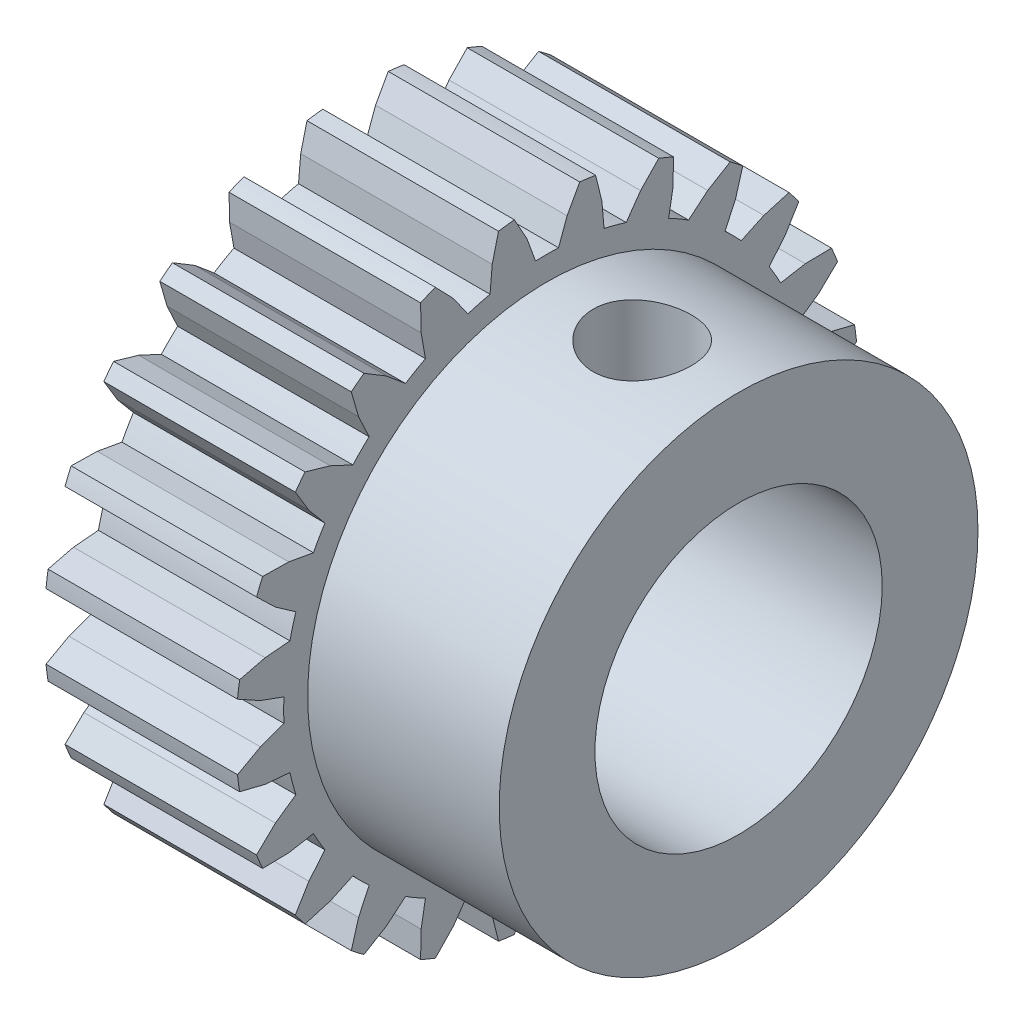
SolidWorks part; units mm, degrees
material "Plain Carbon Steel"
ref_plane "Front Plane" through (0, 0, 0) normal (0, 0, 1) x (1, 0, 0)
ref_plane "Top Plane" through (0, 0, 0) normal (0, 1, 0) x (1, 0, 0)
ref_plane "Right Plane" through (0, 0, 0) normal (1, 0, 0) x (0, 0, -1)
ref_plane "Plane1" through (2, 0, 0) normal (1, 0, 0) x (0, 0, -1)
sketch "Sketch1" plane through (2, 0, 0) normal (1, 0, 0) x (0, 0, -1)
  line L0 (-5.4948, -0.2399) -> (-5.9854, -0.4185)
  line L1 (-5.9854, -0.4185) -> (-6.464, -0.6829)
  line L2 (-6.4205, -1.0134) -> (-5.8898, -1.1449)
  line L3 (-5.8898, -1.1449) -> (-5.3696, -1.1904)
  line L4 (-5.2454, -1.6539) -> (-5.6731, -1.9534)
  line L5 (-5.6731, -1.9534) -> (-6.067, -2.3326)
  line L6 (-5.9395, -2.6406) -> (-5.3927, -2.6303)
  line L7 (-5.3927, -2.6303) -> (-4.8786, -2.5396)
  line L8 (-4.6387, -2.9551) -> (-4.9743, -3.3551)
  line L9 (-4.9743, -3.3551) -> (-5.2566, -3.8234)
  line L10 (-5.0536, -4.0879) -> (-4.5282, -3.9364)
  line L11 (-4.5282, -3.9364) -> (-4.055, -3.7157)
  line L12 (-3.7157, -4.055) -> (-3.9364, -4.5282)
  line L13 (-3.9364, -4.5282) -> (-4.0879, -5.0536)
  line L14 (-3.8234, -5.2566) -> (-3.3551, -4.9743)
  line L15 (-3.3551, -4.9743) -> (-2.9551, -4.6387)
  line L16 (-2.5396, -4.8786) -> (-2.6303, -5.3927)
  line L17 (-2.6303, -5.3927) -> (-2.6406, -5.9395)
  line L18 (-2.3326, -6.067) -> (-1.9534, -5.6731)
  line L19 (-1.9534, -5.6731) -> (-1.6539, -5.2454)
  line L20 (-1.1904, -5.3696) -> (-1.1449, -5.8898)
  line L21 (-1.1449, -5.8898) -> (-1.0134, -6.4205)
  line L22 (-0.6829, -6.464) -> (-0.4185, -5.9854)
  line L23 (-0.4185, -5.9854) -> (-0.2399, -5.4948)
  line L24 (0.2399, -5.4948) -> (0.4185, -5.9854)
  line L25 (0.4185, -5.9854) -> (0.6829, -6.464)
  line L26 (1.0134, -6.4205) -> (1.1449, -5.8898)
  line L27 (1.1449, -5.8898) -> (1.1904, -5.3696)
  line L28 (1.6539, -5.2454) -> (1.9534, -5.6731)
  line L29 (1.9534, -5.6731) -> (2.3326, -6.067)
  line L30 (2.6406, -5.9395) -> (2.6303, -5.3927)
  line L31 (2.6303, -5.3927) -> (2.5396, -4.8786)
  line L32 (2.9551, -4.6387) -> (3.3551, -4.9743)
  line L33 (3.3551, -4.9743) -> (3.8234, -5.2566)
  line L34 (4.0879, -5.0536) -> (3.9364, -4.5282)
  line L35 (3.9364, -4.5282) -> (3.7157, -4.055)
  line L36 (4.055, -3.7157) -> (4.5282, -3.9364)
  line L37 (4.5282, -3.9364) -> (5.0536, -4.0879)
  line L38 (5.2566, -3.8234) -> (4.9743, -3.3551)
  line L39 (4.9743, -3.3551) -> (4.6387, -2.9551)
  line L40 (4.8786, -2.5396) -> (5.3927, -2.6303)
  line L41 (5.3927, -2.6303) -> (5.9395, -2.6406)
  line L42 (6.067, -2.3326) -> (5.6731, -1.9534)
  line L43 (5.6731, -1.9534) -> (5.2454, -1.6539)
  line L44 (5.3696, -1.1904) -> (5.8898, -1.1449)
  line L45 (5.8898, -1.1449) -> (6.4205, -1.0134)
  line L46 (6.464, -0.6829) -> (5.9854, -0.4185)
  line L47 (5.9854, -0.4185) -> (5.4948, -0.2399)
  line L48 (5.4948, 0.2399) -> (5.9854, 0.4185)
  line L49 (5.9854, 0.4185) -> (6.464, 0.6829)
  line L50 (6.4205, 1.0134) -> (5.8898, 1.1449)
  line L51 (5.8898, 1.1449) -> (5.3696, 1.1904)
  line L52 (5.2454, 1.6539) -> (5.6731, 1.9534)
  line L53 (5.6731, 1.9534) -> (6.067, 2.3326)
  line L54 (5.9395, 2.6406) -> (5.3927, 2.6303)
  line L55 (5.3927, 2.6303) -> (4.8786, 2.5396)
  line L56 (4.6387, 2.9551) -> (4.9743, 3.3551)
  line L57 (4.9743, 3.3551) -> (5.2566, 3.8234)
  line L58 (5.0536, 4.0879) -> (4.5282, 3.9364)
  line L59 (4.5282, 3.9364) -> (4.055, 3.7157)
  line L60 (3.7157, 4.055) -> (3.9364, 4.5282)
  line L61 (3.9364, 4.5282) -> (4.0879, 5.0536)
  line L62 (3.8234, 5.2566) -> (3.3551, 4.9743)
  line L63 (3.3551, 4.9743) -> (2.9551, 4.6387)
  line L64 (2.5396, 4.8786) -> (2.6303, 5.3927)
  line L65 (2.6303, 5.3927) -> (2.6406, 5.9395)
  line L66 (2.3326, 6.067) -> (1.9534, 5.6731)
  line L67 (1.9534, 5.6731) -> (1.6539, 5.2454)
  line L68 (1.1904, 5.3696) -> (1.1449, 5.8898)
  line L69 (1.1449, 5.8898) -> (1.0134, 6.4205)
  line L70 (0.6829, 6.464) -> (0.4185, 5.9854)
  line L71 (0.4185, 5.9854) -> (0.2399, 5.4948)
  line L72 (-0.2399, 5.4948) -> (-0.4185, 5.9854)
  line L73 (-0.4185, 5.9854) -> (-0.6829, 6.464)
  line L74 (-1.0134, 6.4205) -> (-1.1449, 5.8898)
  line L75 (-1.1449, 5.8898) -> (-1.1904, 5.3696)
  line L76 (-1.6539, 5.2454) -> (-1.9534, 5.6731)
  line L77 (-1.9534, 5.6731) -> (-2.3326, 6.067)
  line L78 (-2.6406, 5.9395) -> (-2.6303, 5.3927)
  line L79 (-2.6303, 5.3927) -> (-2.5396, 4.8786)
  line L80 (-2.9551, 4.6387) -> (-3.3551, 4.9743)
  line L81 (-3.3551, 4.9743) -> (-3.8234, 5.2566)
  line L82 (-4.0879, 5.0536) -> (-3.9364, 4.5282)
  line L83 (-3.9364, 4.5282) -> (-3.7157, 4.055)
  line L84 (-4.055, 3.7157) -> (-4.5282, 3.9364)
  line L85 (-4.5282, 3.9364) -> (-5.0536, 4.0879)
  line L86 (-5.2566, 3.8234) -> (-4.9743, 3.3551)
  line L87 (-4.9743, 3.3551) -> (-4.6387, 2.9551)
  line L88 (-4.8786, 2.5396) -> (-5.3927, 2.6303)
  line L89 (-5.3927, 2.6303) -> (-5.9395, 2.6406)
  line L90 (-6.067, 2.3326) -> (-5.6731, 1.9534)
  line L91 (-5.6731, 1.9534) -> (-5.2454, 1.6539)
  line L92 (-5.3696, 1.1904) -> (-5.8898, 1.1449)
  line L93 (-5.8898, 1.1449) -> (-6.4205, 1.0134)
  line L94 (-6.464, 0.6829) -> (-5.9854, 0.4185)
  line L95 (-5.9854, 0.4185) -> (-5.4948, 0.2399)
  arc A0 (-6.464, -0.6829) -> (-6.4205, -1.0134) centre (0, 0) ccw
  arc A1 (-5.3696, -1.1904) -> (-5.2454, -1.6539) centre (0, 0) ccw
  arc A2 (-6.067, -2.3326) -> (-5.9395, -2.6406) centre (0, 0) ccw
  arc A3 (-4.8786, -2.5396) -> (-4.6387, -2.9551) centre (0, 0) ccw
  arc A4 (-5.2566, -3.8234) -> (-5.0536, -4.0879) centre (0, 0) ccw
  arc A5 (-4.055, -3.7157) -> (-3.7157, -4.055) centre (0, 0) ccw
  arc A6 (-4.0879, -5.0536) -> (-3.8234, -5.2566) centre (0, 0) ccw
  arc A7 (-2.9551, -4.6387) -> (-2.5396, -4.8786) centre (0, 0) ccw
  arc A8 (-2.6406, -5.9395) -> (-2.3326, -6.067) centre (0, 0) ccw
  arc A9 (-1.6539, -5.2454) -> (-1.1904, -5.3696) centre (0, 0) ccw
  arc A10 (-1.0134, -6.4205) -> (-0.6829, -6.464) centre (0, 0) ccw
  arc A11 (-0.2399, -5.4948) -> (0.2399, -5.4948) centre (0, 0) ccw
  arc A12 (0.6829, -6.464) -> (1.0134, -6.4205) centre (0, 0) ccw
  arc A13 (1.1904, -5.3696) -> (1.6539, -5.2454) centre (0, 0) ccw
  arc A14 (2.3326, -6.067) -> (2.6406, -5.9395) centre (0, 0) ccw
  arc A15 (2.5396, -4.8786) -> (2.9551, -4.6387) centre (0, 0) ccw
  arc A16 (3.8234, -5.2566) -> (4.0879, -5.0536) centre (0, 0) ccw
  arc A17 (3.7157, -4.055) -> (4.055, -3.7157) centre (0, 0) ccw
  arc A18 (5.0536, -4.0879) -> (5.2566, -3.8234) centre (0, 0) ccw
  arc A19 (4.6387, -2.9551) -> (4.8786, -2.5396) centre (0, 0) ccw
  arc A20 (5.9395, -2.6406) -> (6.067, -2.3326) centre (0, 0) ccw
  arc A21 (5.2454, -1.6539) -> (5.3696, -1.1904) centre (0, 0) ccw
  arc A22 (6.4205, -1.0134) -> (6.464, -0.6829) centre (0, 0) ccw
  arc A23 (5.4948, -0.2399) -> (5.4948, 0.2399) centre (0, 0) ccw
  arc A24 (6.464, 0.6829) -> (6.4205, 1.0134) centre (0, 0) ccw
  arc A25 (5.3696, 1.1904) -> (5.2454, 1.6539) centre (0, 0) ccw
  arc A26 (6.067, 2.3326) -> (5.9395, 2.6406) centre (0, 0) ccw
  arc A27 (4.8786, 2.5396) -> (4.6387, 2.9551) centre (0, 0) ccw
  arc A28 (5.2566, 3.8234) -> (5.0536, 4.0879) centre (0, 0) ccw
  arc A29 (4.055, 3.7157) -> (3.7157, 4.055) centre (0, 0) ccw
  arc A30 (4.0879, 5.0536) -> (3.8234, 5.2566) centre (0, 0) ccw
  arc A31 (2.9551, 4.6387) -> (2.5396, 4.8786) centre (0, 0) ccw
  arc A32 (2.6406, 5.9395) -> (2.3326, 6.067) centre (0, 0) ccw
  arc A33 (1.6539, 5.2454) -> (1.1904, 5.3696) centre (0, 0) ccw
  arc A34 (1.0134, 6.4205) -> (0.6829, 6.464) centre (0, 0) ccw
  arc A35 (0.2399, 5.4948) -> (-0.2399, 5.4948) centre (0, 0) ccw
  arc A36 (-0.6829, 6.464) -> (-1.0134, 6.4205) centre (0, 0) ccw
  arc A37 (-1.1904, 5.3696) -> (-1.6539, 5.2454) centre (0, 0) ccw
  arc A38 (-2.3326, 6.067) -> (-2.6406, 5.9395) centre (0, 0) ccw
  arc A39 (-2.5396, 4.8786) -> (-2.9551, 4.6387) centre (0, 0) ccw
  arc A40 (-3.8234, 5.2566) -> (-4.0879, 5.0536) centre (0, 0) ccw
  arc A41 (-3.7157, 4.055) -> (-4.055, 3.7157) centre (0, 0) ccw
  arc A42 (-5.0536, 4.0879) -> (-5.2566, 3.8234) centre (0, 0) ccw
  arc A43 (-4.6387, 2.9551) -> (-4.8786, 2.5396) centre (0, 0) ccw
  arc A44 (-5.9395, 2.6406) -> (-6.067, 2.3326) centre (0, 0) ccw
  arc A45 (-5.2454, 1.6539) -> (-5.3696, 1.1904) centre (0, 0) ccw
  arc A46 (-6.4205, 1.0134) -> (-6.464, 0.6829) centre (0, 0) ccw
  arc A47 (-5.4948, 0.2399) -> (-5.4948, -0.2399) centre (0, 0) ccw
extrude "Boss-Extrude1" add sketch "Sketch1" against normal blind 4
sketch "Sketch2" plane through (0, 0, 0) normal (0, 0, 1) x (1, 0, 0)
  line L0 (2, 5) -> (2, 0)
  line L1 (2, 0) -> (6, 0)
  line L2 (6, 0) -> (6, 5)
  line L3 (6, 5) -> (2, 5)
  line L4 (2, 0) -> (6, 0) construction
revolve "Revolve1" add sketch "Sketch2" angle 360 about L4
hole_wizard "Ø6.0 (6) Diameter Hole1" positions "Sketch4" profile "Sketch3" hole size "Ø6.0" standard "ANSI Metric" end condition through all
sketch "Sketch4" plane through (6, 0, 0) normal (1, 0, 0) x (0, 0, -1)
  point P0 (0, 0)
sketch "Sketch3" plane through (6, 0, 0) normal (0, 1, 0) x (0, 0, -1)
  line L0 (0, 0) -> (0, 8)
  line L1 (0, 8) -> (3, 8)
  line L2 (3, 8) -> (3, 0)
  line L5 (3, 0) -> (0, 0)
  line L11 (0, -6.35) -> (0, 107.95) construction
  dimension "Thru Hole Dia." = 6
  dimension "Thru Hole Depth" = 8
ref_plane "Plane2" through (0, 2.8726, 0.0075) normal (0, -1, -0.0026) x (-1, 0, 0)
hole_wizard "M2.5x0.45 Tapped Hole1" positions "Sketch6" profile "Sketch5" tap size "M2.5x0.45" standard "ANSI Metric"
sketch "Sketch6" plane through (0, 2.8726, 0.0075) normal (0, -1, -0.0026) x (-1, 0, 0)
  point P0 (-4, 0)
sketch "Sketch5" plane through (4, 2.8726, 0.0075) normal (1, 0, 0) x (0, 0.0026, -1)
  line L0 (0, 0) -> (0, 2.1274)
  line L1 (0, 2.1274) -> (1.025, 2.1274)
  line L2 (1.025, 2.1274) -> (1.025, 0)
  line L5 (1.025, 0) -> (0, 0)
  line L11 (0, -6.35) -> (0, 107.95) construction
  dimension "Thread Major Dia." = 2.05
  dimension "Thru Tap Drill Depth" = 2.1274
